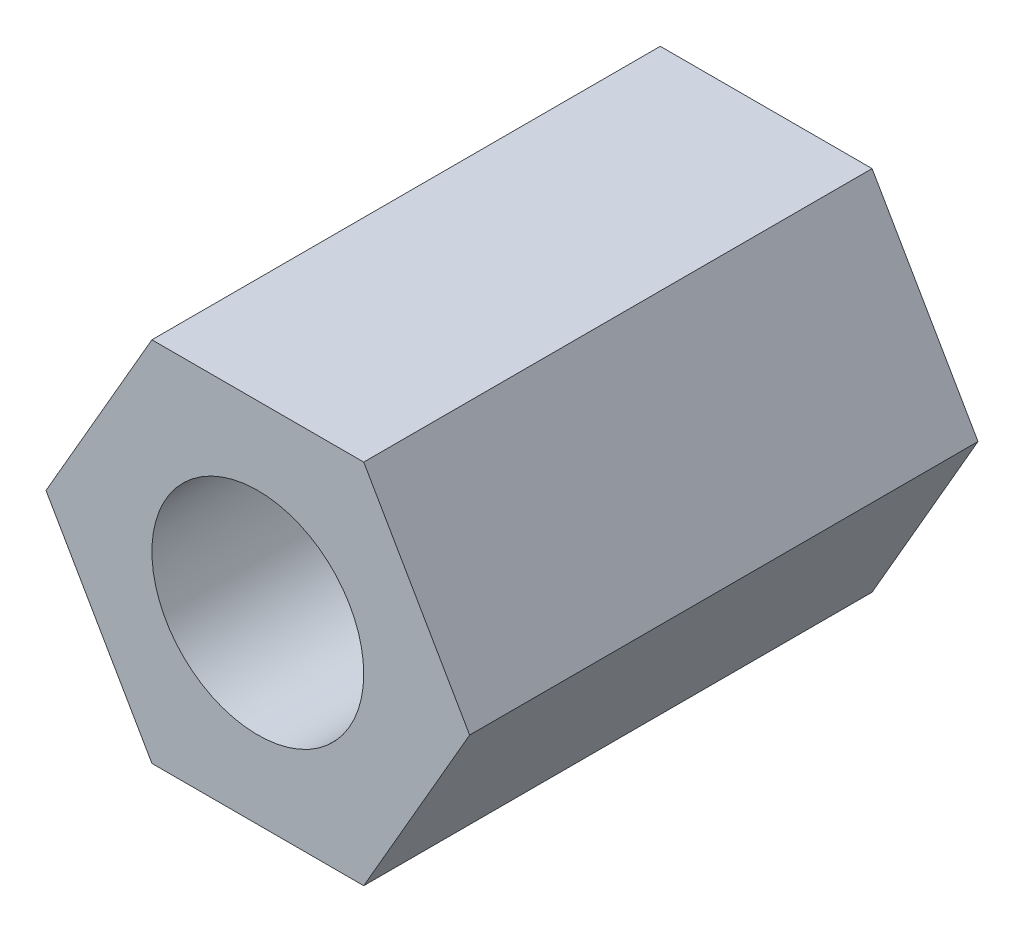
SolidWorks part; units mm, degrees
material "普通碳钢"
ref_plane "前视" through (0, 0, 0) normal (0, 0, 1) x (1, 0, 0)
ref_plane "上视" through (0, 0, 0) normal (0, 1, 0) x (1, 0, 0)
ref_plane "右视" through (0, 0, 0) normal (1, 0, 0) x (0, 0, -1)
sketch "草图1" plane through (0, 0, 0) normal (0, 0, 1) x (1, 0, 0)
  line L0 (0, 0) -> (2.5, 0)
  line L1 (2.5, 0) -> (3.75, -2.1651)
  line L2 (3.75, -2.1651) -> (2.5, -4.3301)
  line L3 (2.5, -4.3301) -> (0, -4.3301)
  line L4 (0, -4.3301) -> (-1.25, -2.1651)
  line L5 (-1.25, -2.1651) -> (0, 0)
  dimension "D1" = 5
  dimension "D2" = 5
extrude "凸台-拉伸1" add sketch "草图1" along normal blind 6
hole_wizard "M3 螺纹孔1" positions "草图3" profile "草图2" tap size "M3" standard "GB" end condition through all
sketch "草图3" plane through (0, 0, 6) normal (0, 0, 1) x (1, 0, 0)
  line L0 (-1.25, -2.1651) -> (3.75, -2.1651) construction
  line L2 (1.25, 0) -> (1.25, -4.3301) construction
  line L3 (2.5, 0) -> (0, 0) construction
  line L4 (0, -4.3301) -> (2.5, -4.3301) construction
  point P0 (1.25, -2.1651)
cosmetic thread "孔螺蚊线1" parameters "D2"=3
sketch "草图2" plane through (1.25, -2.1651, 6) normal (1, 0, 0) x (0, -1, 0)
  line L0 (0, 0) -> (0, 6)
  line L1 (0, 6) -> (1.25, 6)
  line L2 (1.25, 6) -> (1.25, 0)
  line L5 (1.25, 0) -> (0, 0)
  line L11 (0, -6.35) -> (0, 107.95) construction
  dimension "通孔螺纹孔钻头直径" = 2.5
  dimension "通孔螺纹孔钻头深度" = 6
